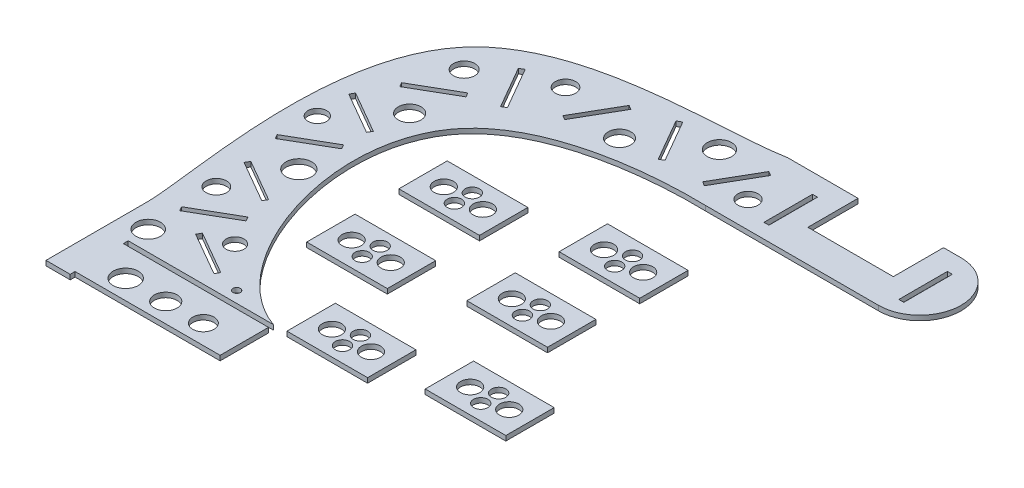
SolidWorks part; units mm, degrees
ref_plane "前视基准面" through (0, 0, 0) normal (0, 0, 1) x (1, 0, 0)
ref_plane "上视基准面" through (0, 0, 0) normal (0, 1, 0) x (1, 0, 0)
ref_plane "右视基准面" through (0, 0, 0) normal (1, 0, 0) x (0, 0, -1)
sketch "草图1" plane through (0, 0, 0) normal (0, 1, 0) x (1, 0, 0)
  line L0 (5.247, -15.0518) -> (5.247, -12.0518)
  line L2 (-9.753, 48.938) -> (-9.753, -15.0518)
  line L3 (-9.753, -15.0518) -> (5.247, -15.0518)
  line L9 (5.247, 17.9482) -> (5.247, 20.9482)
  line L10 (5.247, -12.0518) -> (95.247, -12.0518)
  line L12 (5.247, 17.9482) -> (95.247, 17.9482)
  line L13 (95.247, -12.0518) -> (95.247, 17.9482)
  line L15 (5.247, 20.9482) -> (55.247, 20.9482)
  line L19 (261.747, 218.9482) -> (208.747, 218.9482)
  line L21 (261.747, 238.9482) -> (208.747, 238.9482)
  line L23 (5.247, -12.0518) -> (5.247, -15.0518)
  line L24 (195.5501, 258.1073) -> (192.4501, 258.1073)
  line L25 (261.747, 218.9482) -> (272.6046, 218.9482)
  line L26 (261.747, 238.9482) -> (261.747, 270.0813)
  line L27 (261.747, 270.0813) -> (272.6046, 270.0813)
  line L29 (208.747, 218.9482) -> (165.197, 218.9482)
  line L30 (208.747, 238.9482) -> (208.747, 270.0813)
  line L31 (208.747, 270.0813) -> (165.197, 270.0813)
  line L33 (144.7224, 178.6978) -> (194.7224, 178.6978)
  line L34 (144.7224, 178.6978) -> (144.7224, 148.6978)
  line L35 (144.7224, 148.6978) -> (194.7224, 148.6978)
  line L36 (194.7224, 178.6978) -> (194.7224, 148.6978)
  line L44 (55.247, 20.9482) -> (95.247, 20.9482)
  line L45 (5.247, 20.9482) -> (5.247, 17.9482)
  line L46 (208.747, 238.9482) -> (235.247, 238.9482)
  line L47 (278.806, 258.4988) -> (275.706, 258.4988)
  line L48 (278.806, 258.4988) -> (278.806, 228.3988)
  line L49 (278.806, 228.3988) -> (275.706, 228.3988)
  line L50 (275.706, 258.4988) -> (275.706, 228.3988)
  line L51 (195.5501, 258.1073) -> (195.5501, 228.0073)
  line L52 (195.5501, 228.0073) -> (192.4501, 228.0073)
  line L53 (192.4501, 258.1073) -> (192.4501, 228.0073)
  line L70 (169.3956, 255.2576) -> (166.7109, 256.8076)
  line L71 (169.3956, 255.2576) -> (154.3456, 229.1902)
  line L72 (154.3456, 229.1902) -> (151.6609, 230.7402)
  line L73 (166.7109, 256.8076) -> (151.6609, 230.7402)
  line L74 (90.5299, 247.4409) -> (87.8452, 248.9909)
  line L75 (90.5299, 247.4409) -> (75.4799, 221.3735)
  line L76 (75.4799, 221.3735) -> (72.7952, 222.9235)
  line L77 (87.8452, 248.9909) -> (72.7952, 222.9235)
  line L90 (113.4147, 256.7256) -> (110.73, 255.1756)
  line L91 (113.4147, 256.7256) -> (128.4647, 230.6582)
  line L92 (128.4647, 230.6582) -> (125.78, 229.1082)
  line L93 (110.73, 255.1756) -> (125.78, 229.1082)
  line L94 (36.2647, 236.1083) -> (33.58, 234.5583)
  line L95 (36.2647, 236.1083) -> (51.3147, 210.041)
  line L96 (51.3147, 210.041) -> (48.63, 208.491)
  line L97 (33.58, 234.5583) -> (48.63, 208.491)
  line L102 (0.6127, 101.6276) -> (-0.9373, 98.9429)
  line L103 (0.6127, 101.6276) -> (26.6801, 86.5776)
  line L104 (26.6801, 86.5776) -> (25.1301, 83.8929)
  line L105 (-0.9373, 98.9429) -> (25.1301, 83.8929)
  line L106 (-3.6137, 170.8134) -> (-5.1637, 168.1287)
  line L107 (-3.6137, 170.8134) -> (22.4537, 155.7634)
  line L108 (22.4537, 155.7634) -> (20.9037, 153.0787)
  line L109 (-5.1637, 168.1287) -> (20.9037, 153.0787)
  line L110 (31.1448, 68.1487) -> (29.5948, 70.8334)
  line L111 (31.1448, 68.1487) -> (5.0774, 53.0987)
  line L112 (5.0774, 53.0987) -> (3.5274, 55.7834)
  line L113 (29.5948, 70.8334) -> (3.5274, 55.7834)
  line L114 (22.0181, 136.5377) -> (20.4681, 139.2224)
  line L115 (22.0181, 136.5377) -> (-4.0493, 121.4877)
  line L116 (-4.0493, 121.4877) -> (-5.5993, 124.1724)
  line L117 (20.4681, 139.2224) -> (-5.5993, 124.1724)
  line L118 (32.6977, 202.9931) -> (31.1477, 205.6778)
  line L119 (32.6977, 202.9931) -> (6.6303, 187.9431)
  line L120 (6.6303, 187.9431) -> (5.0803, 190.6278)
  line L121 (31.1477, 205.6778) -> (5.0803, 190.6278)
  line L122 (24.1516, 48.0765) -> (22.6016, 45.3918)
  line L123 (24.1516, 48.0765) -> (50.9984, 32.5765)
  line L124 (50.9984, 32.5765) -> (49.4484, 29.8918)
  line L125 (22.6016, 45.3918) -> (49.4484, 29.8918)
  line L146 (144.7224, 178.6978) -> (194.7224, 148.6978) construction
  line L147 (194.7224, 178.6978) -> (144.7224, 148.6978) construction
  line L148 (169.7224, 163.6978) -> (203.7224, 163.6978) construction
  line L149 (169.7224, 163.6978) -> (169.7224, 187.1637) construction
  line L150 (142.4439, 123.7753) -> (192.4439, 123.7753)
  line L151 (142.4439, 123.7753) -> (142.4439, 93.7753)
  line L152 (142.4439, 93.7753) -> (192.4439, 93.7753)
  line L153 (192.4439, 123.7753) -> (192.4439, 93.7753)
  line L154 (142.4439, 123.7753) -> (192.4439, 93.7753) construction
  line L155 (192.4439, 123.7753) -> (142.4439, 93.7753) construction
  line L156 (167.4439, 108.7753) -> (201.4439, 108.7753) construction
  line L157 (167.4439, 108.7753) -> (167.4439, 132.2412) construction
  line L158 (61.2471, 162.7861) -> (111.2471, 162.7861)
  line L159 (61.2471, 162.7861) -> (61.2471, 132.7861)
  line L160 (61.2471, 132.7861) -> (111.2471, 132.7861)
  line L161 (111.2471, 162.7861) -> (111.2471, 132.7861)
  line L162 (61.2471, 162.7861) -> (111.2471, 132.7861) construction
  line L163 (111.2471, 162.7861) -> (61.2471, 132.7861) construction
  line L164 (86.2471, 147.7861) -> (120.2471, 147.7861) construction
  line L165 (86.2471, 147.7861) -> (86.2471, 171.252) construction
  line L166 (61.2471, 105.6308) -> (111.2471, 105.6308)
  line L167 (61.2471, 105.6308) -> (61.2471, 75.6308)
  line L168 (61.2471, 75.6308) -> (111.2471, 75.6308)
  line L169 (111.2471, 105.6308) -> (111.2471, 75.6308)
  line L170 (61.2471, 105.6308) -> (111.2471, 75.6308) construction
  line L171 (111.2471, 105.6308) -> (61.2471, 75.6308) construction
  line L172 (86.2471, 90.6308) -> (120.2471, 90.6308) construction
  line L173 (86.2471, 90.6308) -> (86.2471, 114.0967) construction
  line L174 (102.9795, 51.6508) -> (152.9795, 51.6508)
  line L175 (102.9795, 51.6508) -> (102.9795, 21.6508)
  line L176 (102.9795, 21.6508) -> (152.9795, 21.6508)
  line L177 (152.9795, 51.6508) -> (152.9795, 21.6508)
  line L178 (102.9795, 51.6508) -> (152.9795, 21.6508) construction
  line L179 (152.9795, 51.6508) -> (102.9795, 21.6508) construction
  line L180 (127.9795, 36.6508) -> (161.9795, 36.6508) construction
  line L181 (127.9795, 36.6508) -> (127.9795, 60.1167) construction
  line L182 (176.9185, 63.4447) -> (226.9185, 63.4447)
  line L183 (176.9185, 63.4447) -> (176.9185, 33.4447)
  line L184 (176.9185, 33.4447) -> (226.9185, 33.4447)
  line L185 (226.9185, 63.4447) -> (226.9185, 33.4447)
  line L186 (176.9185, 63.4447) -> (226.9185, 33.4447) construction
  line L187 (226.9185, 63.4447) -> (176.9185, 33.4447) construction
  line L188 (201.9185, 48.4447) -> (235.9185, 48.4447) construction
  line L189 (201.9185, 48.4447) -> (201.9185, 71.9107) construction
  arc A0 (272.6046, 218.9482) -> (272.6046, 270.0813) centre (272.6046, 244.5148) ccw
  circle A1 centre (58.4361, 238.9482) radius 6.308
  circle A2 centre (102.5526, 228.3288) radius 7.0205
  circle A3 centre (139.579, 253.2915) radius 7.5458
  circle A4 centre (175.2267, 235.3493) radius 6.1927
  circle A5 centre (17.4708, 217.053) radius 6.5792
  circle A6 centre (24.05, 176.6785) radius 7.0657
  circle A7 centre (-3.1637, 146.6362) radius 5.7984
  circle A8 centre (19.7092, 112.3097) radius 7.9767
  circle A9 centre (3.5274, 77.2946) radius 6.3352
  circle A10 centre (40.1125, 52.3193) radius 5.5259
  circle A11 centre (5.247, 33.3559) radius 7.5952
  circle A12 centre (72.7952, 0) radius 6.5768
  circle A13 centre (24.6016, 0) radius 7.7726
  circle A14 centre (49.4484, 0) radius 7.066
  circle A15 centre (65.5388, 27.919) radius 2.2716
  circle A18 centre (181.8376, 163.6978) radius 5.9745
  circle A19 centre (169.7224, 169.2587) radius 4.4691
  circle A20 centre (157.6072, 163.6978) radius 5.9745
  circle A21 centre (169.7224, 158.1368) radius 4.4691
  circle A22 centre (179.559, 108.7753) radius 5.9745
  circle A23 centre (167.4439, 114.3363) radius 4.4691
  circle A24 centre (155.3287, 108.7753) radius 5.9745
  circle A25 centre (167.4439, 103.2144) radius 4.4691
  circle A26 centre (98.3623, 147.7861) radius 5.9745
  circle A27 centre (86.2471, 153.347) radius 4.4691
  circle A28 centre (74.1319, 147.7861) radius 5.9745
  circle A29 centre (86.2471, 142.2251) radius 4.4691
  circle A30 centre (98.3623, 90.6308) radius 5.9745
  circle A31 centre (86.2471, 96.1917) radius 4.4691
  circle A32 centre (74.1319, 90.6308) radius 5.9745
  circle A33 centre (86.2471, 85.0698) radius 4.4691
  circle A34 centre (140.0947, 36.6508) radius 5.9745
  circle A35 centre (127.9795, 42.2117) radius 4.4691
  circle A36 centre (115.8643, 36.6508) radius 5.9745
  circle A37 centre (127.9795, 31.0899) radius 4.4691
  circle A38 centre (214.0337, 48.4447) radius 5.9745
  circle A39 centre (201.9185, 54.0057) radius 4.4691
  circle A40 centre (189.8033, 48.4447) radius 5.9745
  circle A41 centre (201.9185, 42.8838) radius 4.4691
  spline S0 degree 3 poles (165.197, 270.0813) (127.1699, 262.9853) (-54.1636, 278.3128) (-10.6891, 80.196) (-9.753, 48.938) knots 0 0 0 0 0.477547 1 1 1 1
  spline S1 degree 3 poles (165.197, 218.9482) (131.683, 219.7915) (-12.9487, 207.3402) (45.1438, 38.717) (95.247, 20.9482) knots 0 0 0 0 0.406592 1 1 1 1
  dimension "D12" = 50
  dimension "D2" = 30.1
  dimension "D3" = 3
  dimension "D4" = 3.1
  dimension "D5" = 15
  dimension "D6" = 30
  dimension "D7" = 90
  dimension "D8" = 3
  dimension "D9" = 53
  dimension "D10" = 50
  dimension "D11" = 30
  dimension "D13" = 30
  dimension "D14" = 50
  dimension "D15" = 30
  dimension "D16" = 40
  dimension "D17" = 50
  dimension "D18" = 30
  dimension "D19" = 50
  dimension "D20" = 30
  dimension "D21" = 50
  dimension "D22" = 30
  dimension "D23" = 3.1
  dimension "D24" = 30.1
  dimension "D25" = 3.1
  dimension "D26" = 30.1
  dimension "D27" = 3.1
  dimension "D28" = 30.1
  dimension "D29" = 3.1
  dimension "D30" = 30.1
  dimension "D31" = 3.1
  dimension "D32" = 30.1
  dimension "D33" = 30.1
  dimension "D34" = 3.1
  dimension "D35" = 3.1
  dimension "D36" = 30.1
  dimension "D37" = 3.1
  dimension "D38" = 30.1
  dimension "D39" = 30.1
  dimension "D40" = 3.1
  dimension "D41" = 3.1
  dimension "D42" = 30.1
  dimension "D43" = 3.1
  dimension "D44" = 31
extrude "凸台-拉伸1" add sketch "草图1" along normal blind 3 contours S1 L29 L19 L25 A0 L27 L26 L21 L30 L31 S0 L2 L3 L0 L10 L13 L12 L9 L15 L44 A15 A14 A13 A12 A11 A10 A9 A8 A7 A6 A5 A4 A3 A2 A1 | L169 L166 L167 L168 A32 A31 A30 A33 | L161 L158 L159 L160 A28 A27 A26 A29 | L36 L33 L34 L35 A20 A19 A18 A21 | L153 L150 L151 L152 A24 A23 A22 A25 | L177 L174 L175 L176 A36 A35 A34 A37 | L185 L182 L183 L184 A40 A39 A38 A41
